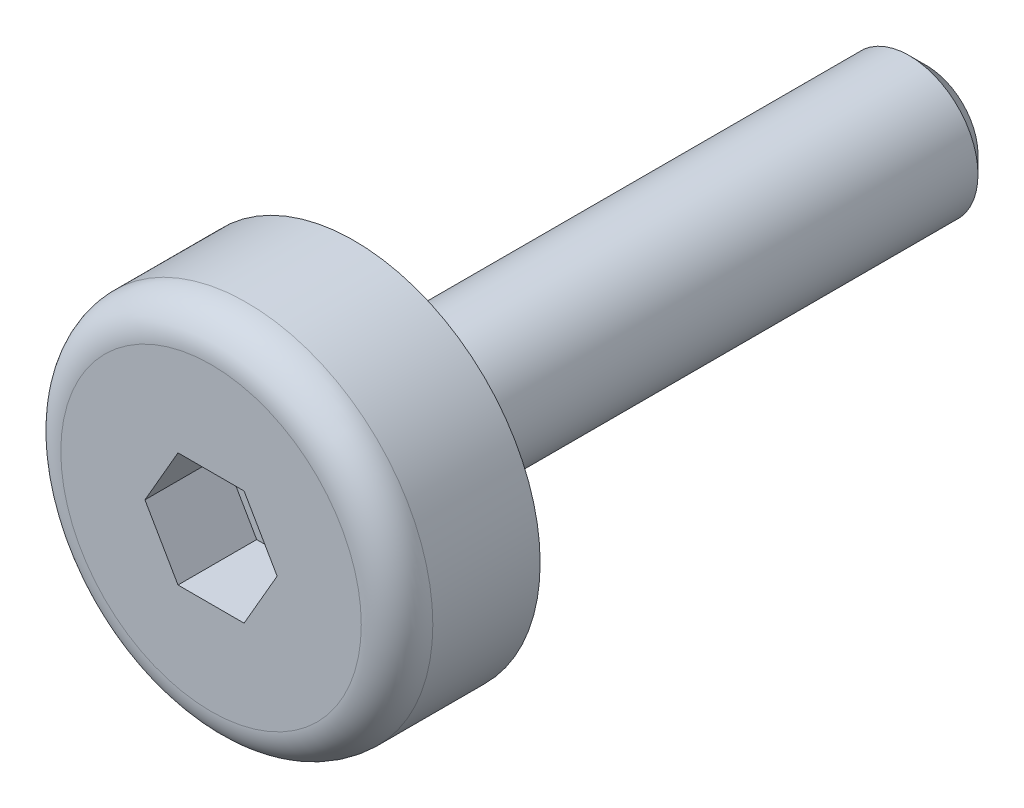
SolidWorks part; units mm, degrees
ref_plane "Front Plane" through (0, 0, 0) normal (0, 0, 1) x (1, 0, 0)
ref_plane "Top Plane" through (0, 0, 0) normal (0, 1, 0) x (1, 0, 0)
ref_plane "Right Plane" through (0, 0, 0) normal (1, 0, 0) x (0, 0, -1)
sketch "Screw Section" plane through (0, 0, 0) normal (0, 1, 0) x (1, 0, 0)
  line L0 (0, 10) -> (1.2, 10)
  line L1 (1.2, 10) -> (1.2, 0)
  line L2 (1.2, 0) -> (3.25, 0)
  line L3 (3.25, 0) -> (3.25, -2.5)
  line L4 (3.25, -2.5) -> (0, -2.5)
  line L5 (0, -2.5) -> (0, 10)
  line L6 (0, -10.123) -> (0, 10.123) construction
  dimension "D1" = 1.2
  dimension "D2" = 3.25
  dimension "D3" = 10
  dimension "D4" = 2.5
  dimension "D5" = 10.123
  dimension "D6" = 10.123
revolve "Screw Blank Revolve" add sketch "Screw Section" angle 360 about L6
chamfer "Shank Tip Chamfer" distance 0.3 1 edges at (1.2, 0, -10)
fillet "Pan Head Round" radius 0.625 1 edges at (3.25, 0, 2.5)
ref_plane "Head Crown Plane" through (0, 0, 2.5) normal (0, 0, 1) x (1, 0, 0)
sketch "Hex Drive Sketch" plane through (0, 0, 2.5) normal (0, 0, 1) x (1, 0, 0)
  line L1 (1.1547, 0) -> (0.5774, 1)
  line L2 (0.5774, 1) -> (-0.5774, 1)
  line L3 (-0.5774, 1) -> (-1.1547, 0)
  line L4 (-1.1547, 0) -> (-0.5774, -1)
  line L5 (-0.5774, -1) -> (0.5774, -1)
  line L6 (0.5774, -1) -> (1.1547, 0)
  circle A0 centre (0, 0) radius 1 construction
  dimension "D1" = 2
extrude "Hex Drive Cut" cut sketch "Hex Drive Sketch" against normal blind 1.375
equation "\"nominal_length\"= 10.0mm 'Screw length: under pan head or including flat head"
equation "\"model_shank_radius\"= 1.2mm 'Clearance envelope minor shank radius; thread is not modeled"
equation "\"head_diameter\"= 6.5mm 'Head outside diameter"
equation "\"head_height\"= 2.5mm 'Head axial height"
equation "\"drive_across_flats\"= 2mm 'Hex drive across flats"
equation "\"tip_chamfer\"= 0.3mm 'Shank tip chamfer"
equation "\"head_round\"= 0.625mm 'Pan head crown edge radius"
equation "\"drive_depth\"= 1.375mm 'Hex socket depth"
equation "\"axis_reference_halfspan\"= 10.123mm 'Half display length of the construction axis; avoids sharing a profile endpoint"
equation "\"D1@Screw Section\"= \"model_shank_radius\""
equation "\"D2@Screw Section\"= \"head_diameter\" / 2"
equation "\"D3@Screw Section\"= \"nominal_length\""
equation "\"D4@Screw Section\"= \"head_height\""
equation "\"D5@Screw Section\"= \"axis_reference_halfspan\""
equation "\"D6@Screw Section\"= \"axis_reference_halfspan\""
equation "\"full_turn\"= 360deg 'Full circular extent for revolves and patterns"
equation "\"D1@Screw Blank Revolve\"= \"full_turn\""
equation "\"D1@Shank Tip Chamfer\"= \"tip_chamfer\""
equation "\"D1@Pan Head Round\"= \"head_round\""
equation "\"D1@Head Crown Plane\"= \"head_height\""
equation "\"D1@Hex Drive Sketch\"= \"drive_across_flats\""
equation "\"D1@Hex Drive Cut\"= \"drive_depth\""
